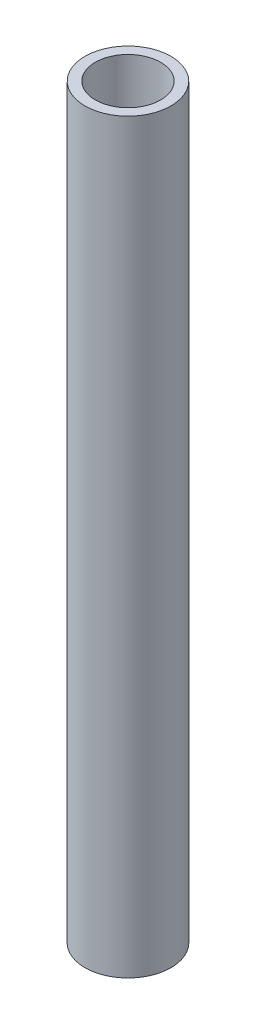
SolidWorks part; units mm, degrees
ref_plane "Спереди" through (0, 0, 0) normal (0, 0, 1) x (1, 0, 0)
ref_plane "Сверху" through (0, 0, 0) normal (0, 1, 0) x (1, 0, 0)
ref_plane "Справа" through (0, 0, 0) normal (1, 0, 0) x (0, 0, -1)
sketch "Эскиз1" plane through (0, 0, 0) normal (0, 1, 0) x (1, 0, 0)
  circle A0 centre (0, 0) radius 12.5
  circle A1 centre (0, 0) radius 9.5
  dimension "D1" = 3
  dimension "D2" = 25
extrude "Бобышка-Вытянуть1" add sketch "Эскиз1" along normal blind 217
sketch "Эскиз2" plane through (0, 0, 0) normal (0, 0, 1) x (1, 0, 0)
  line L0 (12.5, 217) -> (-12.5, 217) construction
  circle A0 centre (0, 202) radius 3
  dimension "D1" = 6
  dimension "D2" = 15
extrude "Вырез-Вытянуть1" cut sketch "Эскиз2" against normal through all
